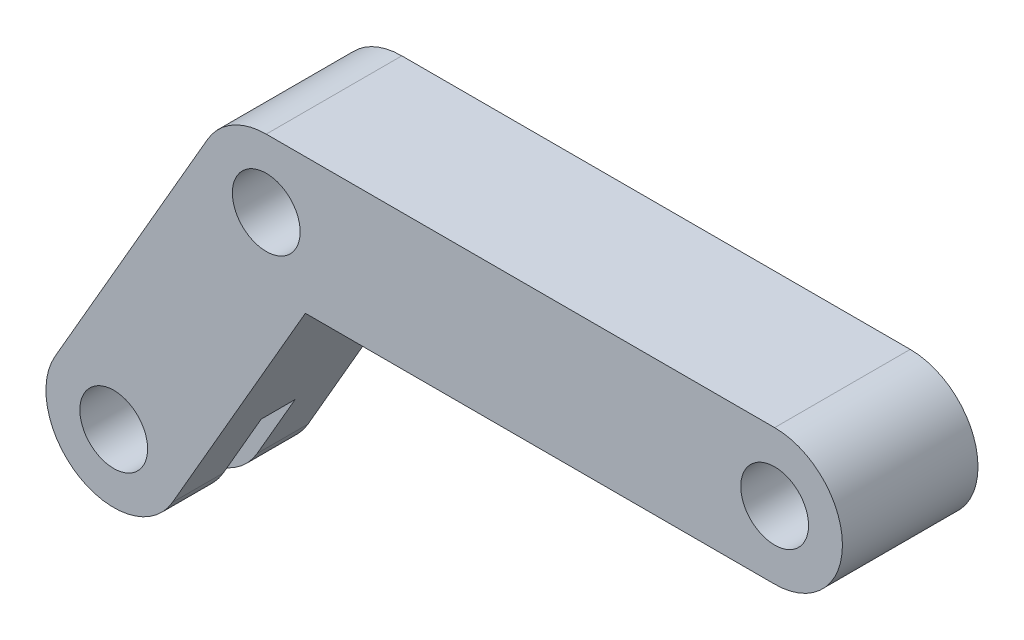
SolidWorks part; units mm, degrees
ref_plane "Front Plane" through (0, 0, 0) normal (0, 0, 1) x (1, 0, 0)
ref_plane "Top Plane" through (0, 0, 0) normal (0, 1, 0) x (1, 0, 0)
ref_plane "Right Plane" through (0, 0, 0) normal (1, 0, 0) x (0, 0, -1)
sketch "Sketch1" plane through (0, 0, 0) normal (0, 0, 1) x (1, 0, 0)
  line L0 (0, 0) -> (75, 0) construction
  line L1 (0, 0) -> (-22.5, -38.9711) construction
  line L2 (5.7735, -10) -> (75, -10)
  line L3 (5.7735, -10) -> (-13.8397, -43.9711)
  line L4 (0, 10) -> (75, 10)
  line L5 (-8.6603, 5) -> (-31.1603, -33.9711)
  line L6 (-5.7735, 10) -> (75, 10) construction
  line L7 (-5.7735, 10) -> (-31.1603, -33.9711) construction
  arc A0 (75, -10) -> (75, 10) centre (75, 0) ccw
  arc A1 (-13.8397, -43.9711) -> (-31.1603, -33.9711) centre (-22.5, -38.9711) cw
  circle A2 centre (-22.5, -38.9711) radius 5
  circle A3 centre (0, 0) radius 5
  circle A4 centre (75, 0) radius 5
  arc A5 (0, 10) -> (-8.6603, 5) centre (0, 0) ccw
  dimension "D6" = 10
  dimension "D7" = 10
  dimension "D8" = 10
  dimension "D9" = 10
  dimension "D1" = 45
  dimension "D2" = 75
  dimension "D3" = 120
  dimension "D4" = 10
  dimension "D5" = 10
extrude "Boss-Extrude1" add sketch "Sketch1" along normal blind 20
ref_plane "Plane1" through (0, 0, 10) normal (0, 0, -1) x (-1, 0, 0)
sketch "Sketch4" plane through (0, 0, 10) normal (0, 0, -1) x (-1, 0, 0)
  circle A0 centre (22.5, -38.9711) radius 15
  dimension "D1" = 30
extrude "Cut-Extrude1" cut sketch "Sketch4" against normal mid plane 5
